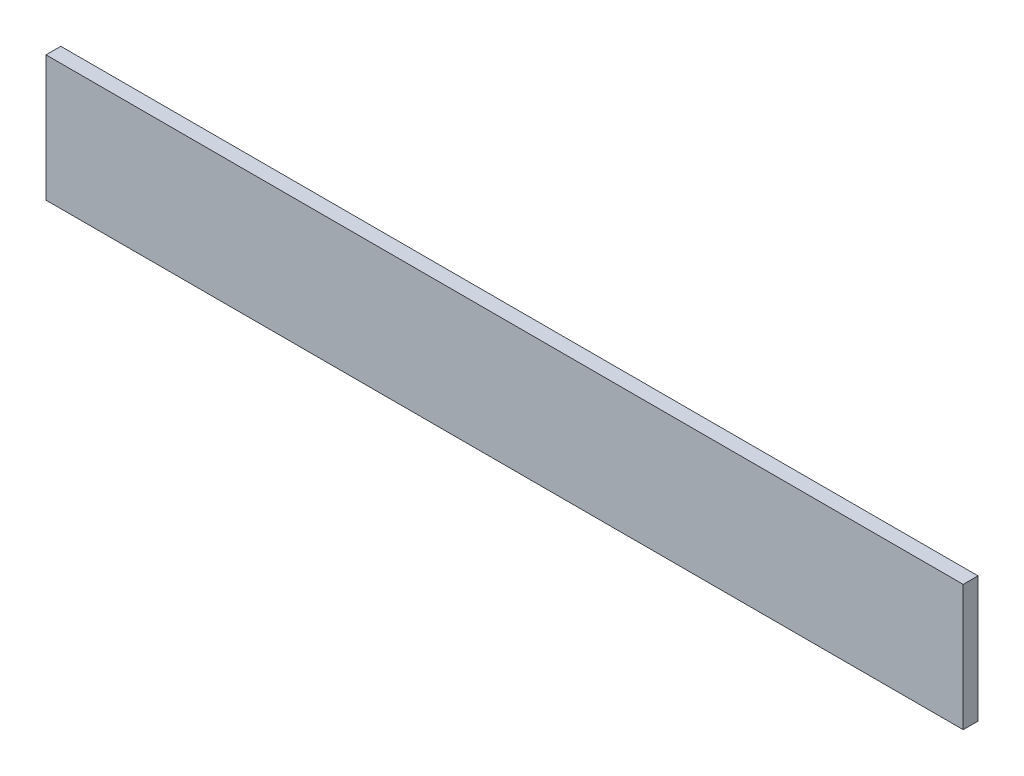
SolidWorks part; units mm, degrees
ref_plane "Front Plane" through (0, 0, 0) normal (0, 0, 1) x (1, 0, 0)
ref_plane "Top Plane" through (0, 0, 0) normal (0, 1, 0) x (1, 0, 0)
ref_plane "Right Plane" through (0, 0, 0) normal (1, 0, 0) x (0, 0, -1)
sketch "Sketch1" plane through (0, 0, 0) normal (0, 0, 1) x (1, 0, 0)
  line L1 (-309.7, 42.5) -> (309.7, 42.5)
  line L2 (-309.7, 42.5) -> (-309.7, -42.5)
  line L3 (-309.7, -42.5) -> (309.7, -42.5)
  line L4 (309.7, 42.5) -> (309.7, -42.5)
  line L5 (-309.7, 42.5) -> (309.7, -42.5) construction
  line L6 (-309.7, -42.5) -> (309.7, 42.5) construction
  point P0 (0, 0)
  dimension "D1" = 85
  dimension "D2" = 619.4
extrude "Boss-Extrude1" add sketch "Sketch1" along normal blind 10
sketch "Sketch2" plane through (0, 0, 0) normal (0, 0, 1) x (1, 0, 0)
  line L1 (-299.7, -32.95) -> (299.7, -32.95)
  line L2 (-299.7, -32.95) -> (-299.7, 32.95)
  line L3 (-299.7, 32.95) -> (299.7, 32.95)
  line L4 (299.7, -32.95) -> (299.7, 32.95)
  line L5 (-299.7, -32.95) -> (299.7, 32.95) construction
  line L6 (-299.7, 32.95) -> (299.7, -32.95) construction
  point P0 (0, 0)
  dimension "D1" = 599.4
  dimension "D2" = 65.9
extrude "Cut-Extrude1" cut sketch "Sketch2" along normal blind 8
